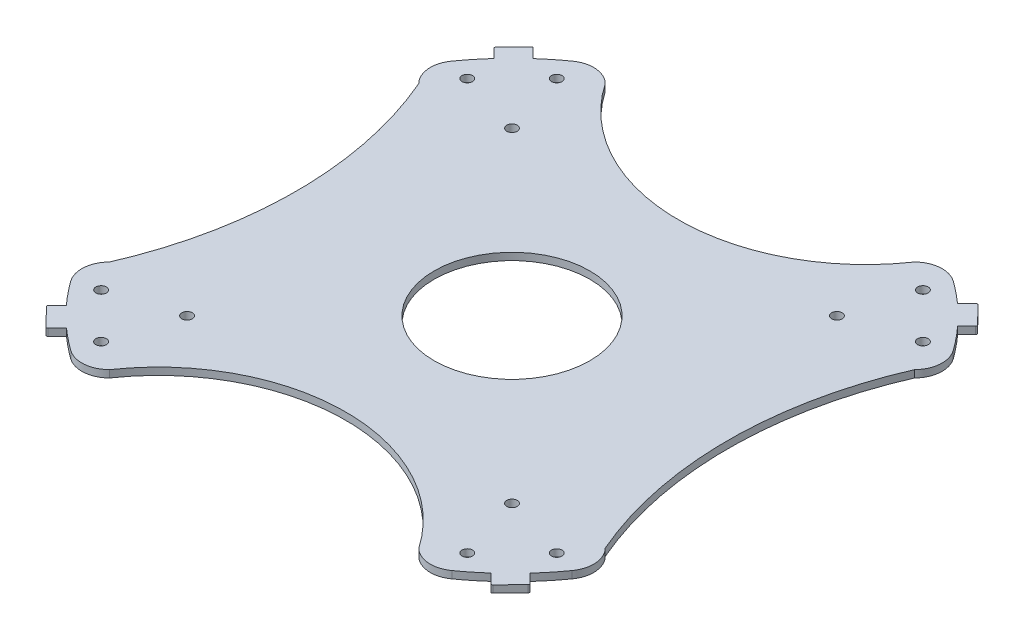
SolidWorks part; units mm, degrees
ref_plane "Front Plane" through (0, 0, 0) normal (0, 0, 1) x (1, 0, 0)
ref_plane "Top Plane" through (0, 0, 0) normal (0, 1, 0) x (1, 0, 0)
ref_plane "Right Plane" through (0, 0, 0) normal (1, 0, 0) x (0, 0, -1)
sketch "Sketch1" plane through (0, 0, 0) normal (0, 1, 0) x (1, 0, 0)
  line L0 (-1000, 0) -> (49000, 0) construction
  line L1 (0, -1000) -> (0, 49000) construction
  line L2 (707.1069, -707.1069) -> (-34648.2322, 34648.2322) construction
  line L3 (-707.1068, -707.1068) -> (34648.2325, 34648.2321) construction
  line L4 (716.0871, -698.1266) -> (0, 17.9605) construction
  line L5 (-698.1265, -716.087) -> (34657.2127, 34639.2518) construction
  line L6 (698.1266, -716.0871) -> (-34657.2125, 34639.2519) construction
  line L7 (-716.087, -698.1265) -> (0, 17.9605) construction
  line L8 (-733.6258, -670.2104) -> (-31.7077, 31.7077) construction
  line L9 (733.9751, -670.5597) -> (22.7274, 40.6879) construction
  line L10 (39.5829, 36.115) -> (36.1358, 39.5583) construction
  line L11 (716.0871, -698.1266) -> (-34639.2519, 34657.2125) construction
  line L12 (35.7817, 39.5534) -> (33.9856, 37.7573) construction
  line L13 (-716.087, -698.1265) -> (34639.2522, 34657.2124) construction
  line L14 (39.5739, 35.7609) -> (37.7573, 33.9856) construction
  line L15 (39.5382, -36.1548) -> (36.0819, -39.6111) construction
  line L16 (39.5078, -35.8322) -> (37.7118, -34.0362) construction
  line L17 (-35.9968, -39.6764) -> (-39.3444, -36.2512) construction
  line L18 (-37.6038, -34.1555) -> (-39.3423, -35.894) construction
  line L19 (35.7129, -39.6171) -> (33.9376, -37.8006) construction
  line L20 (-35.6141, -39.7036) -> (-33.8181, -37.9075) construction
  line L21 (-39.7221, 35.8999) -> (-36.251, 39.2922) construction
  line L22 (-34.2033, 37.5603) -> (-35.8918, 39.2881) construction
  line L24 (-37.9528, 33.7672) -> (-39.7242, 35.5386) construction
  line L25 (-44.6575, -41.2092) -> (-46.396, -42.9477)
  line L26 (-43.0506, -46.7302) -> (-46.3981, -43.3049)
  line L27 (-42.6678, -46.7573) -> (-40.8718, -44.9612)
  line L28 (42.6678, -46.7573) -> (40.8718, -44.9612)
  line L29 (43.0506, -46.7302) -> (46.3981, -43.3049)
  line L30 (-39.4203, -35.9308) -> (-37.6038, -34.1555) [skipped]
  line L31 (-39.7488, 35.5633) -> (-37.9528, 33.7672) [skipped]
  line L32 (-35.9786, 39.3768) -> (-34.2033, 37.5603) [skipped]
  line L33 (44.6575, -41.2092) -> (46.396, -42.9477)
  line L35 (-44.6575, 41.2092) -> (-46.396, 42.9477)
  line L36 (-43.0506, 46.7302) -> (-46.3981, 43.3049)
  line L37 (-42.6678, 46.7573) -> (-40.8718, 44.9612)
  line L38 (44.6575, 41.2092) -> (46.396, 42.9477)
  line L39 (43.0506, 46.7302) -> (46.3981, 43.3049)
  line L40 (42.6678, 46.7573) -> (40.8718, 44.9612)
  arc A0 (-29.6486, 41.2505) -> (-34.2033, 37.5603) centre (0, 0) ccw construction
  arc A1 (-22.7274, 40.6879) -> (-29.6486, 41.2505) centre (-26.519, 36.8963) ccw construction
  arc A2 (-40.6879, 22.7274) -> (-41.2505, 29.6486) centre (-36.8963, 26.519) cw construction
  arc A3 (22.7274, 40.6879) -> (29.6486, 41.2505) centre (26.519, 36.8963) cw construction
  arc A4 (40.6879, 22.7274) -> (41.2505, 29.6486) centre (36.8963, 26.519) ccw construction
  arc A5 (40.6879, -22.7274) -> (41.2505, -29.6486) centre (36.8963, -26.519) cw construction
  arc A6 (22.7274, -40.6879) -> (29.6486, -41.2505) centre (26.519, -36.8963) ccw construction
  arc A7 (-22.7274, -40.6879) -> (-29.6486, -41.2505) centre (-26.519, -36.8963) cw construction
  arc A8 (-40.6879, -22.7274) -> (-41.2505, -29.6486) centre (-36.8963, -26.519) ccw construction
  arc A9 (-22.7274, 40.6879) -> (22.7274, 40.6879) centre (0, 66.2866) ccw construction
  arc A10 (40.6879, 22.7274) -> (40.6879, -22.7274) centre (66.2866, 0) ccw construction
  arc A11 (22.7274, -40.6879) -> (-22.7274, -40.6879) centre (0, -66.2866) ccw construction
  arc A12 (-40.6879, -22.7274) -> (-40.6879, 22.7274) centre (-66.2866, 0) ccw construction
  arc A13 (-29.6486, 41.2505) -> (-34.2033, 37.5603) centre (0, 0) ccw construction
  arc A14 (41.2505, 29.6486) -> (37.7573, 33.9856) centre (0, 0) ccw construction
  arc A15 (41.2505, 29.6486) -> (37.7573, 33.9856) centre (0, 0) ccw construction
  arc A16 (29.6486, -41.2505) -> (33.9376, -37.8006) centre (0, 0) ccw construction
  arc A17 (29.6486, -41.2505) -> (33.9376, -37.8006) centre (0, 0) ccw construction
  arc A18 (-41.2505, -29.6486) -> (-37.6038, -34.1555) centre (0, 0) ccw construction
  arc A19 (-41.2505, -29.6486) -> (-37.6038, -34.1555) centre (0, 0) ccw construction
  arc A20 (33.9856, 37.7573) -> (29.6486, 41.2505) centre (0, 0) ccw construction
  arc A21 (33.9856, 37.7573) -> (29.6486, 41.2505) centre (0, 0) ccw construction
  arc A22 (37.7118, -34.0362) -> (41.2505, -29.6486) centre (0, 0) ccw construction
  arc A23 (37.7118, -34.0362) -> (41.2505, -29.6486) centre (0, 0) ccw construction
  arc A24 (-33.8181, -37.9075) -> (-29.6486, -41.2505) centre (0, 0) ccw construction
  arc A25 (-33.8181, -37.9075) -> (-29.6486, -41.2505) centre (0, 0) ccw construction
  arc A26 (-37.9528, 33.7672) -> (-41.2505, 29.6486) centre (0, 0) ccw construction
  arc A27 (-37.9528, 33.7672) -> (-41.2505, 29.6486) centre (0, 0) ccw construction
  arc A28 (-35.6141, -39.7036) -> (-35.9968, -39.6764) centre (-35.7937, -39.5239) cw construction
  arc A29 (-39.3423, -35.894) -> (-39.3444, -36.2512) centre (-39.1627, -36.0736) ccw construction
  arc A30 (35.7129, -39.6171) -> (36.0819, -39.6111) centre (35.8945, -39.4396) ccw construction
  arc A31 (39.5078, -35.8322) -> (39.5382, -36.1548) centre (39.3282, -36.0118) cw construction
  arc A32 (39.5739, 35.7609) -> (39.5829, 36.115) centre (39.3964, 35.9426) ccw construction
  arc A33 (36.1358, 39.5583) -> (35.7817, 39.5534) centre (35.9613, 39.3738) ccw construction
  arc A34 (-39.7221, 35.8999) -> (-39.7242, 35.5386) centre (-39.5446, 35.7182) ccw construction
  arc A35 (-36.251, 39.2922) -> (-35.8918, 39.2881) centre (-36.0735, 39.1105) cw construction
  circle A36 centre (-28.2202, 36.8412) radius 1.016 construction
  circle A37 centre (-36.8412, 28.2202) radius 1.016 construction
  circle A38 centre (-24.2455, 24.2455) radius 1.016 construction
  circle A39 centre (28.2202, 36.8412) radius 1.016 construction
  circle A40 centre (36.8412, 28.2202) radius 1.016 construction
  circle A41 centre (24.2455, 24.2455) radius 1.016 construction
  circle A42 centre (36.8412, -28.2202) radius 1.016 construction
  circle A43 centre (28.2202, -36.8412) radius 1.016 construction
  circle A44 centre (24.2455, -24.2455) radius 1.016 construction
  circle A45 centre (-28.2202, -36.8412) radius 1.016 construction
  circle A46 centre (-36.8412, -28.2202) radius 1.016 construction
  circle A47 centre (-24.2455, -24.2455) radius 1.016 construction
  circle A48 centre (0, 0) radius 6.1441 construction
  arc A49 (-47.7417, -29.7811) -> (-48.3042, -36.7023) centre (-43.9501, -33.5727) ccw
  arc A50 (-48.3042, -36.7023) -> (-44.6575, -41.2092) centre (-7.0537, -7.0537) ccw
  arc A51 (-42.6678, -46.7573) -> (-43.0506, -46.7302) centre (-42.8474, -46.5777) cw
  arc A52 (-46.396, -42.9477) -> (-46.3981, -43.3049) centre (-46.2164, -43.1273) ccw
  arc A53 (-29.7811, -47.7417) -> (-36.7023, -48.3042) centre (-33.5727, -43.9501) cw
  arc A54 (-40.8718, -44.9612) -> (-36.7023, -48.3042) centre (-7.0537, -7.0537) ccw
  circle A55 centre (-35.2739, -43.8949) radius 1.016
  arc A56 (-40.8718, -44.9612) -> (-36.7023, -48.3042) centre (-7.0537, -7.0537) ccw construction
  circle A57 centre (-43.8949, -35.2739) radius 1.016
  circle A58 centre (-31.2992, -31.2992) radius 1.016
  arc A59 (42.6678, -46.7573) -> (43.0506, -46.7302) centre (42.8474, -46.5777) ccw
  arc A60 (46.396, -42.9477) -> (46.3981, -43.3049) centre (46.2164, -43.1273) cw
  circle A61 centre (43.8949, -35.2739) radius 1.016
  arc A62 (48.3042, -36.7023) -> (44.6575, -41.2092) centre (7.0537, -7.0537) cw
  arc A63 (47.7417, -29.7811) -> (48.3042, -36.7023) centre (43.9501, -33.5727) cw
  arc A64 (29.7811, -47.7417) -> (36.7023, -48.3042) centre (33.5727, -43.9501) ccw
  arc A65 (40.8718, -44.9612) -> (36.7023, -48.3042) centre (7.0537, -7.0537) cw
  circle A66 centre (35.2739, -43.8949) radius 1.016
  circle A67 centre (31.2992, -31.2992) radius 1.016
  arc A68 (-46.396, 42.9477) -> (-46.3981, 43.3049) centre (-46.2164, 43.1273) cw
  arc A69 (-42.6678, 46.7573) -> (-43.0506, 46.7302) centre (-42.8474, 46.5777) ccw
  arc A70 (-40.8718, 44.9612) -> (-36.7023, 48.3042) centre (-7.0537, 7.0537) cw
  arc A71 (-48.3042, 36.7023) -> (-44.6575, 41.2092) centre (-7.0537, 7.0537) cw
  arc A72 (-47.7417, 29.7811) -> (-48.3042, 36.7023) centre (-43.9501, 33.5727) cw
  arc A73 (-29.7811, 47.7417) -> (-36.7023, 48.3042) centre (-33.5727, 43.9501) ccw
  circle A74 centre (-35.2739, 43.8949) radius 1.016
  circle A75 centre (-31.2992, 31.2992) radius 1.016
  circle A76 centre (-43.8949, 35.2739) radius 1.016
  arc A77 (48.3042, 36.7023) -> (44.6575, 41.2092) centre (7.0537, 7.0537) ccw
  arc A78 (47.7417, 29.7811) -> (48.3042, 36.7023) centre (43.9501, 33.5727) ccw
  arc A79 (46.396, 42.9477) -> (46.3981, 43.3049) centre (46.2164, 43.1273) ccw
  arc A80 (42.6678, 46.7573) -> (43.0506, 46.7302) centre (42.8474, 46.5777) cw
  arc A81 (40.8718, 44.9612) -> (36.7023, 48.3042) centre (7.0537, 7.0537) ccw
  arc A82 (29.7811, 47.7417) -> (36.7023, 48.3042) centre (33.5727, 43.9501) cw
  circle A83 centre (43.8949, 35.2739) radius 1.016
  circle A84 centre (35.2739, 43.8949) radius 1.016
  circle A85 centre (31.2992, 31.2992) radius 1.016
  arc A86 (-29.7811, -47.7417) -> (29.7811, -47.7417) centre (0, -68.1673) cw
  arc A87 (29.7811, 47.7417) -> (-29.7811, 47.7417) centre (0, 68.1673) cw
  arc A88 (47.7417, 29.7811) -> (47.7417, -29.7811) centre (116.5754, 0) ccw
  arc A89 (-47.7417, 29.7811) -> (-47.7417, -29.7811) centre (-116.5754, 0) cw
  circle A94 centre (0, 0) radius 15
  point P46 (0, 0)
  point P60 (0, 0)
  point P75 (-0.048, -0.2069)
  point P83 (41.6473, 37.8756)
  point P86 (37.8756, 41.6473)
  point P94 (-39, 24.5)
  point P120 (0, 0)
  point P208 (-39, -24.5)
  point P210 (19, 24.5)
  point P212 (19.003, -24.4994)
  dimension "D1" = 12.7
  dimension "D3" = 4
  dimension "D4" = 4
  dimension "D7" = 0.254
  dimension "D8" = 50.8
  dimension "D10" = 0.254
  dimension "D9" = 0.254
  dimension "D13" = 13.208
  dimension "D15" = 2
  dimension "D16" = 75
  dimension "D5" = 2.667
  dimension "D11" = 12.192
  dimension "D12" = 7.366
  dimension "D2" = 12.7
  dimension "D6" = 4
  dimension "D14" = 4
extrude "Boss-Extrude1" add sketch "Sketch1" along normal blind 1.397
